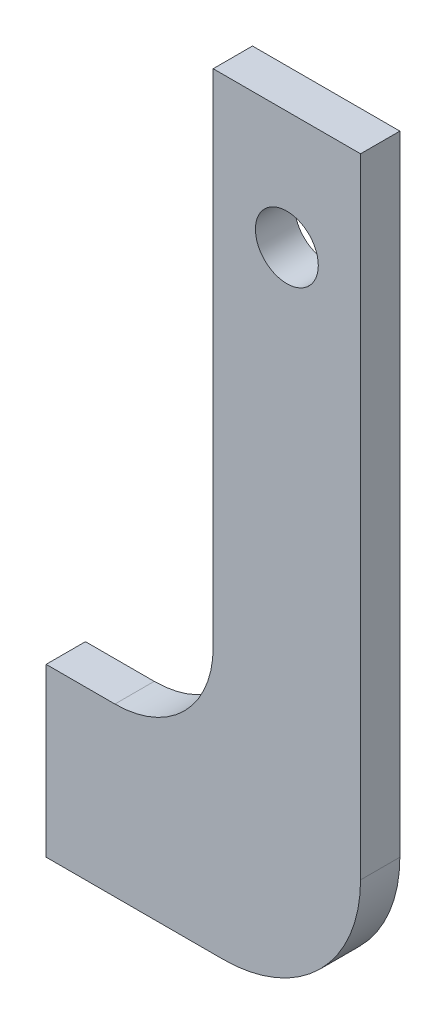
SolidWorks part; units mm, degrees
ref_plane "前视基准面" through (0, 0, 0) normal (0, 0, 1) x (1, 0, 0)
ref_plane "上视基准面" through (0, 0, 0) normal (0, 1, 0) x (1, 0, 0)
ref_plane "右视基准面" through (0, 0, 0) normal (1, 0, 0) x (0, 0, -1)
sketch "草图1" plane through (0, 0, 0) normal (0, 0, 1) x (1, 0, 0)
  line L1 (-11.2387, -1.281) -> (-7.7387, -1.281)
  line L2 (-11.2387, -1.281) -> (-11.2387, -9.781)
  line L3 (-11.2387, -9.781) -> (-2.2387, -9.781)
  line L4 (4.7613, -1.281) -> (4.7613, -2.781)
  line L5 (-2.2387, -9.781) -> (-2.7387, -9.781)
  line L6 (4.7613, -2.781) -> (4.7613, 29.219)
  line L7 (4.7613, 29.219) -> (-2.7387, 29.219)
  line L8 (-2.7387, 3.719) -> (-2.7387, 29.219)
  arc A0 (-7.7387, -1.281) -> (-2.7387, 3.719) centre (-7.7387, 3.719) ccw
  arc A1 (-2.2387, -9.781) -> (4.7613, -2.781) centre (-2.2387, -2.781) ccw
  circle A2 centre (1.0113, 23.219) radius 1.6
  point P14 (1.0113, 29.219)
  dimension "D5" = 5
  dimension "D6" = 7
  dimension "D3" = 3.2
  dimension "D8" = 0
  dimension "D1" = 16
  dimension "D2" = 8.5
  dimension "D4" = 7.5
  dimension "D7" = 6
extrude "凸台-拉伸1" add sketch "草图1" along normal blind 2 contours L3 A1 L4 L6 L7 L8 A0 L1 L2 A2
